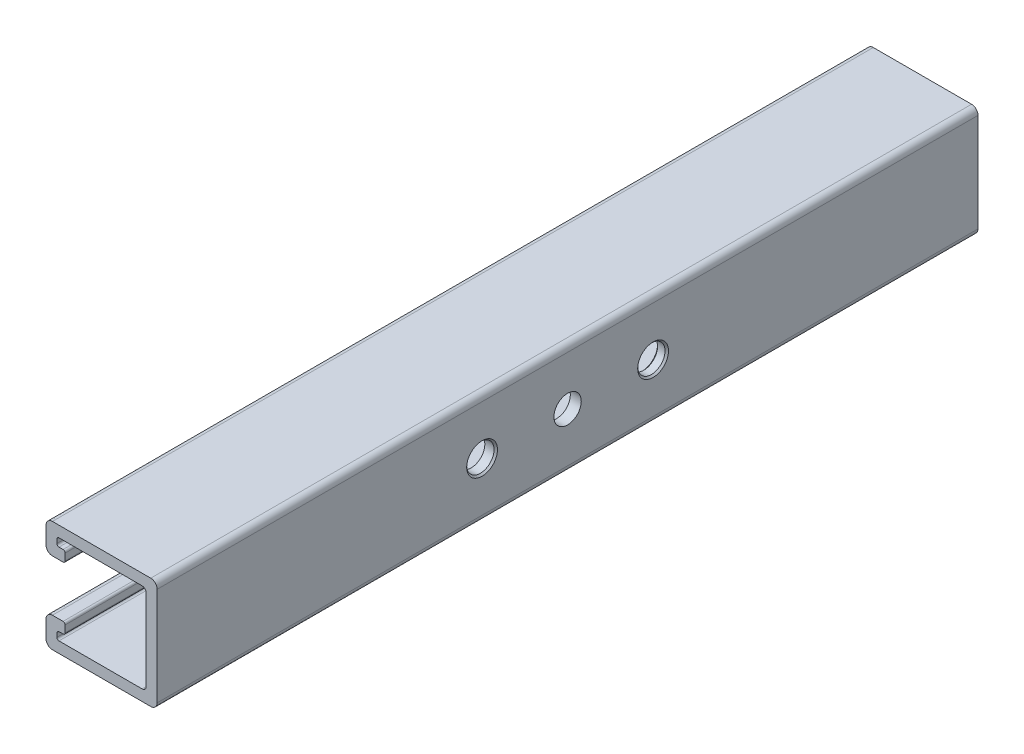
SolidWorks part; units mm, degrees
material "S-Glass Fiber"
ref_plane "Front Plane" through (0, 0, 0) normal (0, 0, 1) x (1, 0, 0)
ref_plane "Top Plane" through (0, 0, 0) normal (0, 1, 0) x (1, 0, 0)
ref_plane "Right Plane" through (0, 0, 0) normal (1, 0, 0) x (0, 0, -1)
sketch "Sketch1" plane through (0, 0, 0) normal (0, 0, 1) x (1, 0, 0)
  line L0 (-13.5255, 9.525) -> (-18.2499, 9.525)
  line L1 (-20.6375, 11.9126) -> (-20.6375, 18.2499)
  line L2 (-18.2499, 20.6375) -> (18.2499, 20.6375)
  line L3 (20.6375, 18.2499) -> (20.6375, -18.2499)
  line L4 (18.2499, -20.6375) -> (-18.2499, -20.6375)
  line L5 (-20.6375, -18.2499) -> (-20.6375, -11.9126)
  line L6 (-18.2499, -9.525) -> (-13.5255, -9.525)
  line L7 (0, 0) -> (20.6375, 0) construction
  line L8 (0, 0) -> (0, 20.6375) construction
  arc A0 (-20.6375, 18.2499) -> (-18.2499, 20.6375) centre (-18.2499, 18.2499) cw
  arc A1 (-18.2499, 9.525) -> (-20.6375, 11.9126) centre (-18.2499, 11.9126) cw
  arc A2 (-20.6375, -11.9126) -> (-18.2499, -9.525) centre (-18.2499, -11.9126) cw
  arc A3 (-18.2499, -20.6375) -> (-20.6375, -18.2499) centre (-18.2499, -18.2499) cw
  arc A4 (20.6375, -18.2499) -> (18.2499, -20.6375) centre (18.2499, -18.2499) cw
  arc A5 (18.2499, 20.6375) -> (20.6375, 18.2499) centre (18.2499, 18.2499) cw
  point P14 (-20.6375, 20.6375)
  point P23 (20.6375, -20.6375)
  point P26 (20.6375, 20.6375)
  dimension "D4" = 2.3876
  dimension "D1" = 41.275
  dimension "D2" = 41.275
  dimension "D3" = 19.05
  dimension "D5" = 7.112
extrude "Extrude-Thin1" add sketch "Sketch1" against normal blind 304.8 thin
fillet "Fillet2" radius 0.762 8 edges at (-16.5735, 13.589, -152.4) (-16.5735, -16.5735, -152.4) (-16.5735, 16.5735, -152.4) (-13.5255, 13.589, -152.4) (-13.5255, 9.525, -152.4) (-13.5255, -9.525, -152.4) (-13.5255, -13.589, -152.4) (-16.5735, -13.589, -152.4)
fillet "Fillet3" radius 1.524 2 edges at (16.5735, 16.5735, -152.4) (16.5735, -16.5735, -152.4)
sketch "Sketch3" plane through (0, 0, 0) normal (1, 0, 0) x (0, 0, -1)
  line L0 (0, 0) -> (304.8, 0) construction
  line L1 (304.8, 18.2499) -> (304.8, -18.2499) construction
  line L2 (0, 0) -> (0, 20.6375) construction
  line L3 (304.8, 0) -> (304.8, 20.6375) construction
  line L4 (304.8, 20.6375) -> (0, 20.6375) construction
  point P3 (101.6, 0)
  point P4 (203.2, 0)
  dimension "D1" = 101.6
  dimension "D2" = 101.6
sketch "Sketch4" plane through (20.6375, 0, 0) normal (1, 0, 0) x (0, 0, -1)
  line L0 (0, 0) -> (304.8, 0) construction
  line L1 (0, 18.2499) -> (0, -18.2499) construction
  line L2 (304.8, 18.2499) -> (304.8, -18.2499) construction
  line L3 (184.15, 5.08) -> (152.4, 5.08) construction
  line L4 (152.4, 5.08) -> (120.65, 5.08) construction
  circle A0 centre (152.4, 0) radius 5.08
  circle A1 centre (184.15, 0) radius 5.08
  circle A2 centre (120.65, 0) radius 5.08
  point P12 (119.8389, 5.08)
  point P16 (170.2292, 5.08)
  point P17 (192.228, 5.08)
  dimension "D1" = 10.16
  dimension "D2" = 10.16
  dimension "D3" = 31.75
extrude "Cut-Extrude1" cut sketch "Sketch4" against normal through all
chamfer "Chamfer1" distance 0.635 angle 45 3 edges at (20.6375, 0, -125.73) (16.5735, 0, -179.07) (20.6375, 0, -189.23)
